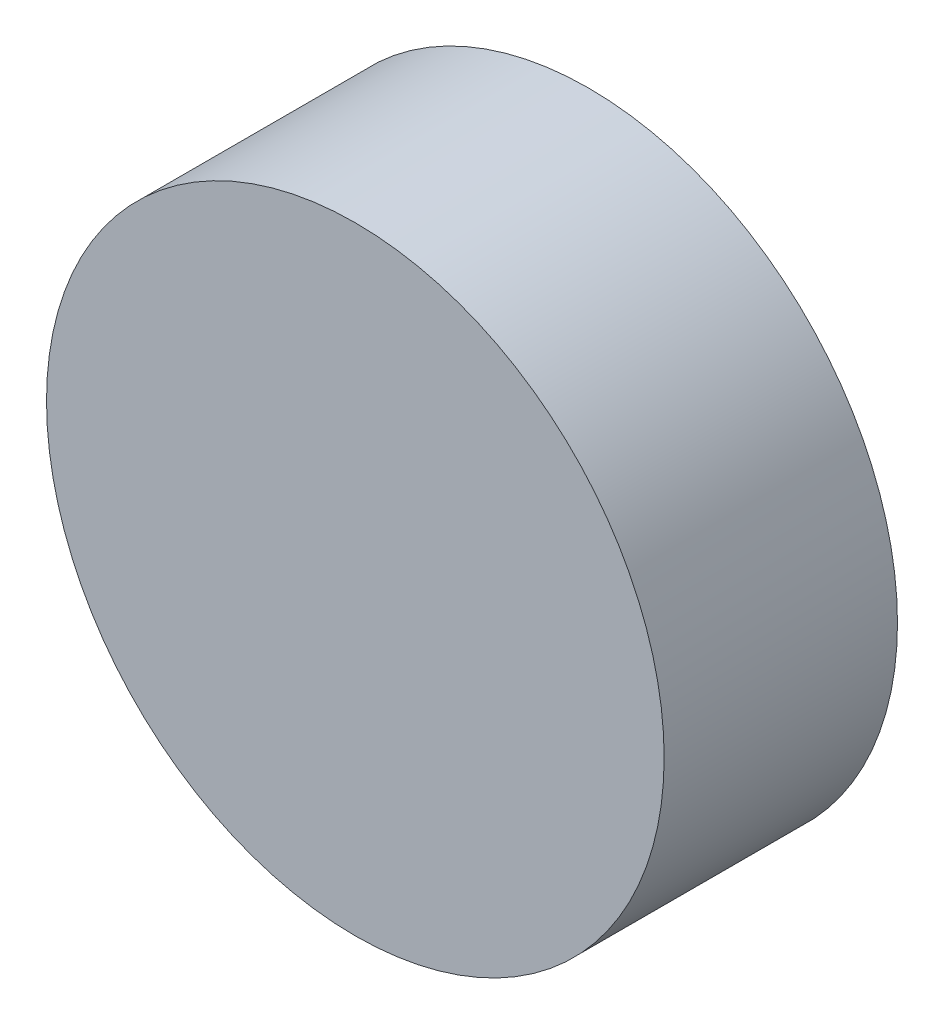
SolidWorks part; units mm, degrees
ref_plane "Front Plane" through (0, 0, 0) normal (0, 0, 1) x (1, 0, 0)
ref_plane "Top Plane" through (0, 0, 0) normal (0, 1, 0) x (1, 0, 0)
ref_plane "Right Plane" through (0, 0, 0) normal (1, 0, 0) x (0, 0, -1)
sketch "Sketch1" plane through (0, 0, 0) normal (0, 0, 1) x (1, 0, 0)
  circle A0 centre (0, 0) radius 2.25
  dimension "D1" = 4.5
extrude "Boss-Extrude1" add sketch "Sketch1" along normal mid plane 1.7
